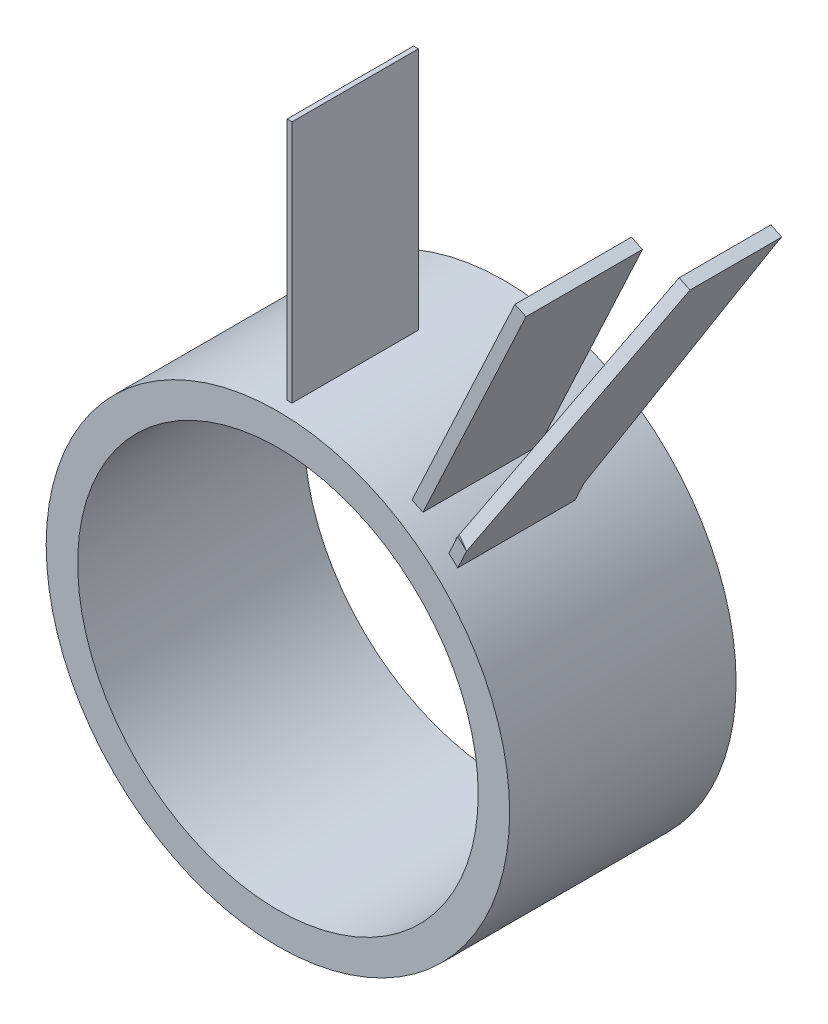
SolidWorks part; units mm, degrees
ref_plane "Front Plane" through (0, 0, 0) normal (0, 0, 1) x (1, 0, 0)
ref_plane "Top Plane" through (0, 0, 0) normal (0, 1, 0) x (1, 0, 0)
ref_plane "Right Plane" through (0, 0, 0) normal (1, 0, 0) x (0, 0, -1)
sketch "Sketch1" plane through (0, 0, 0) normal (0, 0, 1) x (1, 0, 0)
  circle A0 centre (0, 0) radius 34.0548
  circle A1 centre (0, 0) radius 29.4319
extrude "Boss-Extrude1" add sketch "Sketch1" along normal blind 33.274
ref_plane "Plane1" through (0, 34.036, 0) normal (0, 1, 0) x (1, 0, 0)
sketch "Sketch2" plane through (0, 34.036, 0) normal (0, 1, 0) x (1, 0, 0)
  line L5 (-0.7207, -31.2032) -> (0, -31.2032)
  line L6 (-0.7207, -31.2032) -> (-0.7207, -12.624)
  line L7 (-0.7207, -12.624) -> (0, -12.624)
  line L8 (0, -31.2032) -> (0, -12.624)
  line L9 (-0.7207, -31.2032) -> (0, -12.624) construction
  line L10 (-0.7207, -12.624) -> (0, -31.2032) construction
  point P0 (-0.3603, -21.9136)
extrude "Boss-Extrude2" add sketch "Sketch2" along normal blind 35.814
ref_plane "Plane2" through (34.0548, 0, 0) normal (1, 0, 0) x (0, 0, -1)
ref_plane "Plane3" through (14.3922, 30.8642, 0) normal (0.4226, 0.9063, 0) x (0, 0, -1)
sketch "Sketch4" plane through (14.3922, 30.8642, 0) normal (0.4226, 0.9063, 0) x (0, 0, -1)
  line L0 (-13.2772, 14.7945) -> (-13.2772, -3.5696) construction
  line L1 (-13.2772, -3.5696) -> (-30.3912, -3.5696) construction
  line L2 (-30.3912, -3.5696) -> (-31.4115, 14.7945) construction
  line L4 (-13.2772, -2.6741) -> (-30.3912, -2.6741)
  line L5 (-13.2772, -2.6741) -> (-13.2772, -4.4652)
  line L6 (-13.2772, -4.4652) -> (-30.3912, -4.4652)
  line L7 (-30.3912, -2.6741) -> (-30.3912, -4.4652)
  line L8 (-13.2772, -2.6741) -> (-30.3912, -4.4652) construction
  line L9 (-13.2772, -4.4652) -> (-30.3912, -2.6741) construction
  point P2 (-21.8342, -3.5696)
extrude "Boss-Extrude3" add sketch "Sketch4" along normal blind 35.814 separate body
sketch "Sketch5" plane through (14.3922, 30.8642, 0) normal (0.4226, 0.9063, 0) x (0, 0, -1)
  line L1 (-30.4632, -9.3437) -> (-13.2425, -9.3437)
  line L2 (-30.4632, -9.3437) -> (-30.4632, -11.0446)
  line L3 (-30.4632, -11.0446) -> (-13.2425, -11.0446)
  line L4 (-13.2425, -9.3437) -> (-13.2425, -11.0446)
  line L5 (-30.4632, -9.3437) -> (-13.2425, -11.0446) construction
  line L6 (-30.4632, -11.0446) -> (-13.2425, -9.3437) construction
  point P0 (-21.8528, -10.1941)
extrude "Boss-Extrude4" add sketch "Sketch5" along normal blind 3.048 from surface separate body starting at face at (34.0548, 0, 0)
sketch "Sketch6" plane through (10.0098, -4.6676, 0) normal (0.9063, -0.4226, 0) x (0, 0, -1)
  line L0 (-30.4632, 35.2621) -> (-13.2425, 35.2621)
  line L1 (-13.2425, 35.2621) -> (0.5505, 68.9026)
  line L2 (-30.4632, 35.2621) -> (-12.3208, 70.0409)
  line L3 (-12.3208, 70.0409) -> (1.1634, 70.0409)
  line L4 (1.1634, 70.0409) -> (0.5505, 68.9026)
extrude "Boss-Extrude5" add sketch "Sketch6" against normal blind 1.778
